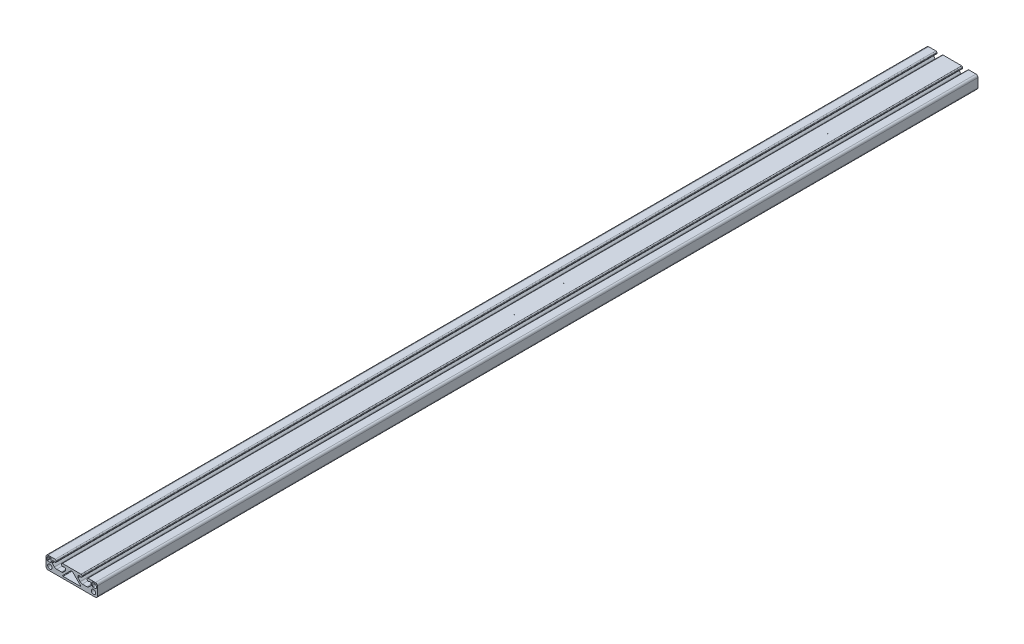
SolidWorks part; units mm, degrees
material "6061 Alloy"
ref_plane "Front Plane" through (0, 0, 0) normal (0, 0, 1) x (1, 0, 0)
ref_plane "Top Plane" through (0, 0, 0) normal (0, 1, 0) x (1, 0, 0)
ref_plane "Right Plane" through (0, 0, 0) normal (1, 0, 0) x (0, 0, -1)
sketch "Sketch1" plane through (0, 0, 0) normal (0, 0, 1) x (1, 0, 0)
  line L0 (0, -10) -> (0, 10) construction
  line L1 (-40, 0) -> (40, 0) construction
  line L2 (-20, -2.3) -> (-20, 13.0699) construction
  line L3 (20, -2.3) -> (20, 13.0699) construction
  line L4 (34.0048, -14.2627) -> (34.0048, 0) construction
  line L5 (-34.0048, -15.6676) -> (-34.0048, 0) construction
  line L6 (-36.8282, 10) -> (-25.7617, 10)
  line L7 (-14.3654, 10) -> (-7.0441, 10)
  line L8 (-7.0441, 10) -> (14.5525, 10)
  line L9 (-34.0048, -4) -> (34.0048, -4) construction
  line L11 (25.4475, 10) -> (33.0758, 10)
  line L12 (-26.8986, 5.9365) -> (-25.7617, 5.9365)
  line L13 (-14.3654, 5.9365) -> (-13.2285, 5.9365)
  line L14 (13.2285, 6.6606) -> (13.2285, 5.9365)
  line L15 (13.2285, 5.9365) -> (14.3654, 5.9365)
  line L16 (10.9848, 6.6606) -> (13.2285, 6.6606)
  line L17 (-23.5072, -2.3) -> (-16.2347, -2.3)
  line L19 (-29.0152, 6.4054) -> (-26.8986, 6.4054)
  line L21 (-36.8282, -10) -> (36.8254, -10)
  line L52 (-38.35, 2.5953) -> (-38.35, 5.5571)
  line L53 (-33.2048, 1.9604) -> (-37.7151, 1.9604)
  line L54 (-31.935, 7.7151) -> (-31.935, 3.2302)
  line L55 (-35.4935, 8.35) -> (-32.5699, 8.35)
  line L57 (13.4502, -6.9544) -> (-13.4502, -6.9544)
  line L58 (0, 6.9552) -> (-0.8088, 6.9553)
  line L59 (-13.8991, -5.8705) -> (-1.2578, 6.7693)
  line L60 (40, 6.8282) -> (40, -6.8282)
  line L61 (33.0758, 10) -> (36.8854, 10)
  line L63 (24.06, 7.5111) -> (24.06, 8.4254)
  line L64 (26.7715, 5.9365) -> (25.6346, 5.9365)
  line L65 (26.7715, 6.6606) -> (26.7715, 5.9365)
  line L66 (29.0152, 6.6606) -> (26.7715, 6.6606)
  line L67 (30.285, 3.1342) -> (30.285, 5.3908)
  line L68 (26.8655, -0.9089) -> (30.0247, 2.2504)
  line L69 (16.4928, -2.3) -> (23.5072, -2.3)
  line L70 (9.9753, 2.5057) -> (13.1345, -0.6536)
  line L71 (9.715, 5.3908) -> (9.715, 3.1342)
  line L75 (15.94, 8.4254) -> (15.94, 7.5111)
  line L79 (13.8991, -5.8705) -> (1.2578, 6.7693)
  line L80 (0, 6.9552) -> (0.8088, 6.9553)
  line L81 (35.5549, 8.35) -> (32.564, 8.35)
  line L82 (31.935, 7.7219) -> (31.935, 3.2459)
  line L83 (33.2048, 1.976) -> (37.6808, 1.976)
  line L84 (38.35, 2.5356) -> (38.35, 5.4968)
  line L88 (-15.94, 8.4254) -> (-15.94, 7.5111)
  line L90 (-13.2285, 5.9365) -> (-13.2285, 6.4054)
  line L91 (-13.2285, 6.4054) -> (-10.9848, 6.4054)
  line L92 (-9.715, 5.1355) -> (-9.715, 2.6208)
  line L93 (-9.9753, 1.9923) -> (-12.8764, -0.9089)
  line L95 (-26.8655, -0.9089) -> (-30.0247, 2.2504)
  line L96 (-30.285, 2.879) -> (-30.285, 5.1355)
  line L98 (-26.8986, 6.4054) -> (-26.8986, 5.9365)
  line L100 (-24.06, 7.506) -> (-24.06, 8.4203)
  line L103 (-40, 6.8282) -> (-40, -6.8282)
  arc A38 (36.8854, 10) -> (40, 6.8282) centre (36.8254, 6.826) cw
  circle A39 centre (-34.0048, -4) radius 3.4
  arc A40 (-38.35, 2.5953) -> (-37.7151, 1.9604) centre (-37.7151, 2.5953) ccw
  arc A41 (-33.2048, 1.9604) -> (-31.935, 3.2302) centre (-33.2048, 3.2302) ccw
  arc A42 (-35.4935, 8.35) -> (-38.35, 5.5571) centre (-35.5563, 5.5571) ccw
  arc A43 (-31.935, 7.7151) -> (-32.5699, 8.35) centre (-32.5699, 7.7151) ccw
  arc A44 (-13.8991, -5.8705) -> (-13.4502, -6.9544) centre (-13.4502, -6.3195) ccw
  arc A45 (-0.8088, 6.9553) -> (-1.2578, 6.7693) centre (-0.8088, 6.3203) ccw
  arc A46 (24.06, 8.4254) -> (25.4475, 10) centre (25.6346, 8.4365) cw
  arc A47 (25.6346, 5.9365) -> (24.06, 7.5111) centre (25.6346, 7.5111) cw
  arc A48 (29.0152, 6.6606) -> (30.285, 5.3908) centre (29.0152, 5.3908) cw
  arc A49 (30.285, 3.1342) -> (30.0247, 2.2504) centre (29.4256, 2.9071) cw
  arc A50 (26.8655, -0.9089) -> (23.5072, -2.3) centre (23.5072, 2.4492) cw
  arc A51 (16.4928, -2.3) -> (13.1345, -0.6536) centre (16.7353, 2.443) cw
  arc A52 (9.9753, 2.5057) -> (9.715, 3.1342) centre (10.6039, 3.1342) cw
  arc A53 (9.715, 5.3908) -> (10.9848, 6.6606) centre (10.9848, 5.3908) cw
  arc A54 (15.94, 7.5111) -> (14.3654, 5.9365) centre (14.3654, 7.5111) cw
  arc A55 (14.5525, 10) -> (15.94, 8.4254) centre (14.3654, 8.4365) cw
  arc A56 (40, -6.8282) -> (36.8254, -10) centre (36.8254, -6.8254) cw
  arc A57 (0.8088, 6.9553) -> (1.2578, 6.7693) centre (0.8088, 6.3203) cw
  arc A58 (13.8991, -5.8705) -> (13.4502, -6.9544) centre (13.4502, -6.3195) cw
  arc A59 (31.935, 7.7219) -> (32.564, 8.35) centre (32.5699, 7.7151) cw
  arc A60 (35.5549, 8.35) -> (38.35, 5.4968) centre (35.557, 5.5563) cw
  arc A61 (33.2048, 1.976) -> (31.935, 3.2459) centre (33.2048, 3.2459) cw
  arc A62 (38.35, 2.5356) -> (37.6808, 1.976) centre (37.7194, 2.6098) cw
  circle A63 centre (34.0048, -4) radius 3.4
  arc A64 (-40, -6.8282) -> (-36.8282, -10) centre (-36.8282, -6.8282) ccw
  arc A65 (-14.3654, 10) -> (-15.94, 8.4254) centre (-14.3654, 8.4254) ccw
  arc A66 (-15.94, 7.5111) -> (-14.3654, 5.9365) centre (-14.3654, 7.5111) ccw
  arc A67 (-9.715, 5.1355) -> (-10.9848, 6.4054) centre (-10.9848, 5.1355) ccw
  arc A68 (-9.9753, 1.9923) -> (-9.715, 2.6208) centre (-10.6039, 2.6208) ccw
  arc A69 (-16.2347, -2.3) -> (-12.8764, -0.9089) centre (-16.2347, 2.4492) ccw
  arc A70 (-26.8655, -0.9089) -> (-23.5072, -2.3) centre (-23.5072, 2.4492) ccw
  arc A71 (-30.285, 2.879) -> (-30.0247, 2.2504) centre (-29.3961, 2.879) ccw
  arc A72 (-29.0152, 6.4054) -> (-30.285, 5.1355) centre (-29.0152, 5.1355) ccw
  arc A73 (-25.7617, 5.9365) -> (-24.06, 7.506) centre (-25.6346, 7.506) ccw
  arc A74 (-24.06, 8.4203) -> (-25.7617, 10) centre (-25.6441, 8.4203) ccw
  arc A75 (-36.8282, 10) -> (-40, 6.8282) centre (-36.8282, 6.8282) ccw
  dimension "D4" = 6.8
  dimension "D1" = 20
  dimension "D2" = 80
  dimension "D3" = 40
  dimension "D5" = 6
  dimension "D6" = 8.12
  dimension "D7" = 4.0635
  dimension "D8" = 20.57
  dimension "D9" = 12.3
  dimension "D10" = 20
extrude "Extrude1" add sketch "Sketch1" against normal blind 1371.6
sketch "Sketch2" plane through (0, -10, 0) normal (0, -1, 0) x (1, 0, 0)
  line L0 (0, -1263.0575) -> (0, -1353.0575) construction
  line L1 (-40, -1371.6) -> (-40, 0) construction
  line L2 (-36.8282, -1371.6) -> (36.8254, -1371.6) construction
  circle A0 centre (-19.935, -1351.6) radius 2.065
  circle A1 centre (-19.935, -1301.6) radius 2.065
  circle A2 centre (19.935, -1301.6) radius 2.065
  circle A3 centre (19.935, -1351.6) radius 2.065
  dimension "D7" = 4.13
  dimension "D8" = 4.13
  dimension "D9" = 4.13
  dimension "D10" = 4.13
  dimension "D1" = 39.87
  dimension "D2" = 39.87
  dimension "D3" = 19.935
  dimension "D4" = 50
  dimension "D5" = 40
  dimension "D6" = 20
extrude "Cut-Extrude1" cut sketch "Sketch2" against normal through all
sketch "Sketch8" plane through (0, -10, 0) normal (0, -1, 0) x (1, 0, 0)
  line L0 (0, 6.1425) -> (0, -83.8575) construction
  line L1 (-36.8282, 0) -> (36.8254, 0) construction
  line L2 (-40, -1371.6) -> (-40, 0) construction
  circle A0 centre (-19.935, -82.4) radius 2.065
  circle A1 centre (-19.935, -32.4) radius 2.065
  circle A2 centre (19.935, -32.4) radius 2.065
  circle A3 centre (19.935, -82.4) radius 2.065
  dimension "D5" = 4.13
  dimension "D6" = 4.13
  dimension "D7" = 4.13
  dimension "D8" = 4.13
  dimension "D1" = 39.87
  dimension "D2" = 39.87
  dimension "D3" = 19.935
  dimension "D4" = 50
  dimension "D9" = 32.4
  dimension "D10" = 40
extrude "Cut-Extrude2" cut sketch "Sketch8" against normal blind 10
